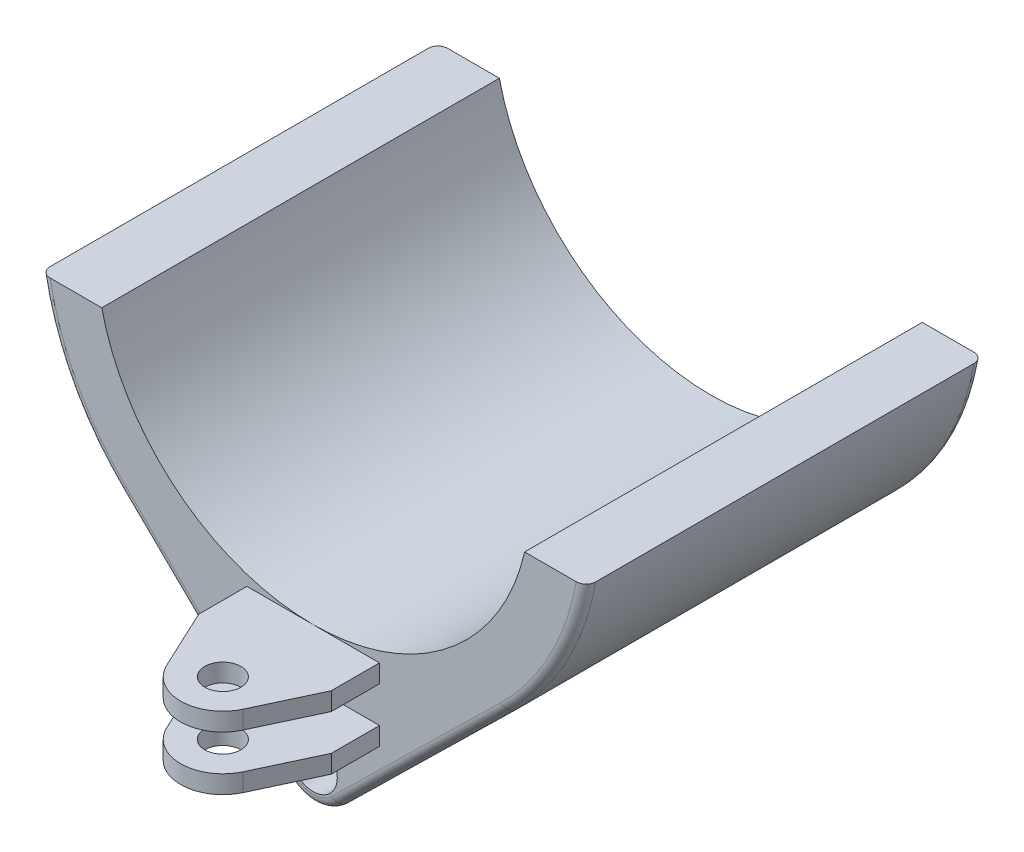
SolidWorks part; units mm, degrees
ref_plane "Front Plane" through (0, 0, 0) normal (0, 0, 1) x (1, 0, 0)
ref_plane "Top Plane" through (0, 0, 0) normal (0, 1, 0) x (1, 0, 0)
ref_plane "Right Plane" through (0, 0, 0) normal (1, 0, 0) x (0, 0, -1)
sketch "Sketch1" plane through (0, 0, 0) normal (0, 0, 1) x (1, 0, 0)
  line L0 (0, 0) -> (0, 280) construction
  line L1 (-226.495, 240) -> (-175.4993, 240)
  line L2 (-160.9665, 115.7143) -> (-20.9956, -21.4286)
  line L3 (160.9665, 115.7143) -> (20.9956, -21.4286)
  line L4 (175.4993, 240) -> (226.495, 240)
  arc A0 (-226.495, 240) -> (-160.9665, 115.7143) centre (0, 280) ccw
  arc A1 (-175.4993, 240) -> (175.4993, 240) centre (0, 280) ccw
  arc A2 (-20.9956, -21.4286) -> (20.9956, -21.4286) centre (0, 0) ccw
  circle A3 centre (0, 0) radius 20
  arc A4 (160.9665, 115.7143) -> (226.495, 240) centre (0, 280) ccw
  dimension "D1" = 460
  dimension "D2" = 360
  dimension "D3" = 60
  dimension "D4" = 40
  dimension "D5" = 40
  dimension "D6" = 240
extrude "Boss-Extrude1" add sketch "Sketch1" along normal mid plane 330
sketch "Sketch2" plane through (0, 0, 0) normal (0, 1, 0) x (1, 0, 0)
  line L0 (0, -165) -> (0, -275) construction
  line L1 (-175.4993, -165) -> (175.4993, -165) construction
  line L2 (-55, -165) -> (55, -165)
  line L3 (55, -165) -> (55, -205)
  line L4 (55, -205) -> (31.7059, -254.8235)
  line L5 (-31.7059, -254.8235) -> (-55, -205)
  line L6 (-55, -205) -> (-55, -165)
  arc A0 (31.7059, -254.8235) -> (-31.7059, -254.8235) centre (0, -240) cw
  circle A1 centre (0, -240) radius 15
  dimension "D4" = 35
  dimension "D6" = 30
  dimension "D1" = 110
  dimension "D2" = 110
  dimension "D3" = 40
  dimension "D5" = 40
extrude "Boss-Extrude2" add sketch "Sketch2" along normal blind 60 from offset 40
sketch "Sketch3" plane through (0, 0, 0) normal (1, 0, 0) x (0, 0, -1)
  line L0 (-165, 100) -> (-165, 40) construction
  line L1 (-165, 85) -> (-371.2398, 85)
  line L2 (-165, 85) -> (-165, 55)
  line L3 (-165, 55) -> (-371.2398, 55)
  line L4 (-371.2398, 85) -> (-371.2398, 55)
  dimension "D1" = 30
  dimension "D2" = 15
extrude "Cut-Extrude1" cut sketch "Sketch3" against normal mid plane 347
sketch "Sketch4" plane through (0, 0, 0) normal (1, 0, 0) x (0, 0, -1)
  line L0 (-165, -21.4286) -> (-165, 115.7143) construction
  line L1 (-105, 95) -> (105, 95)
  line L2 (-105, 95) -> (-105, -75.5174)
  line L3 (-105, -75.5174) -> (105, -75.5174)
  line L4 (105, 95) -> (105, -75.5174)
  line L5 (165, -21.4286) -> (165, 115.7143) construction
  line L6 (-205, 100) -> (-165, 100) construction
  dimension "D1" = 60
  dimension "D2" = 60
  dimension "D3" = 5
extrude "Cut-Extrude2" cut sketch "Sketch4" against normal mid plane 2109
fillet "Fillet1" radius 4 2 edges at (0, 95, -105) (0, 95, 105)
fillet "Fillet2" radius 8 10 edges at (-203.4535, 172.7309, -165) (203.4535, 172.7309, -165) (90.981, 47.1429, -165) (0, -30, -165) (-203.4535, 172.7309, 165) (-90.981, 47.1429, 165) (0, -30, 165) (203.4535, 172.7309, 165) (-90.981, 47.1429, -165) (90.981, 47.1429, 165)
